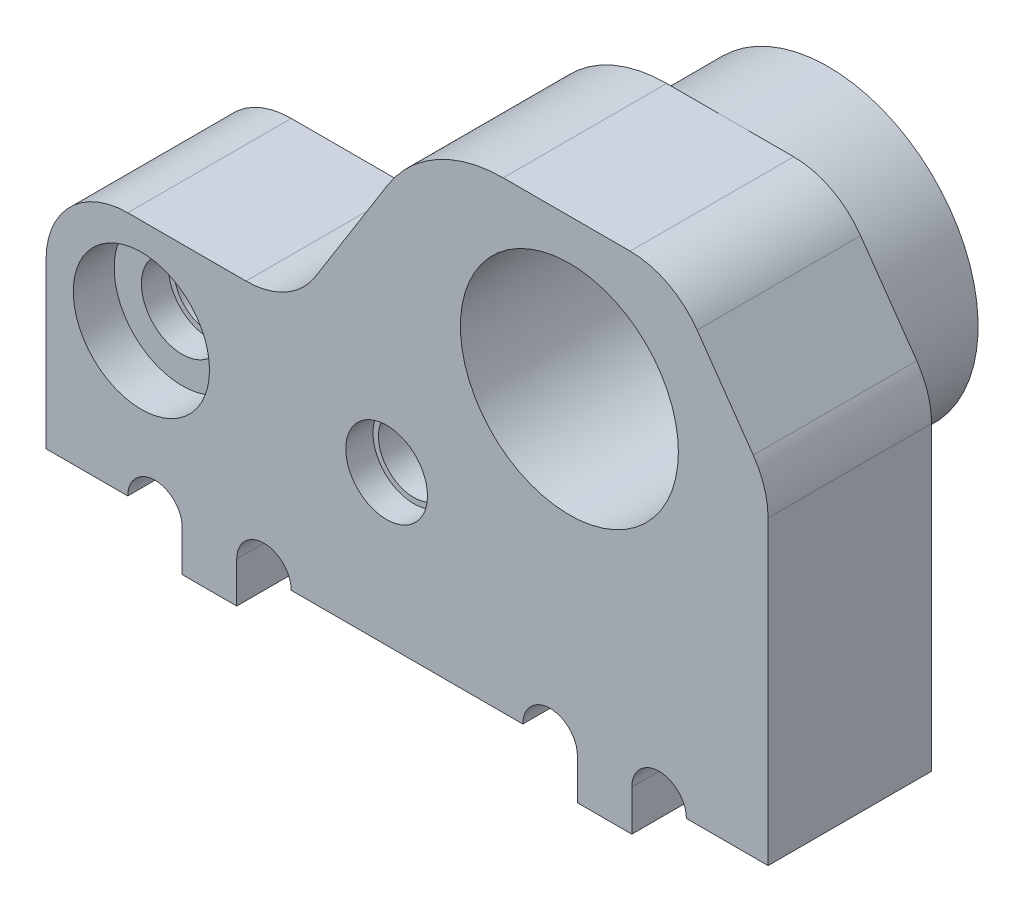
SolidWorks part; units mm, degrees
ref_plane "Front Plane" through (0, 0, 0) normal (0, 0, 1) x (1, 0, 0)
ref_plane "Top Plane" through (0, 0, 0) normal (0, 1, 0) x (1, 0, 0)
ref_plane "Right Plane" through (0, 0, 0) normal (1, 0, 0) x (0, 0, -1)
sketch "Sketch1" plane through (0, 0, 0) normal (0, 1, 0) x (1, 0, 0)
  line L1 (0, 0) -> (26.5, 0)
  line L2 (0, 0) -> (0, 6)
  line L3 (0, 6) -> (26.5, 6)
  line L4 (26.5, 0) -> (26.5, 6)
  dimension "D1" = 26.5
  dimension "D2" = 6
extrude "Boss-Extrude1" add sketch "Sketch1" along normal blind 17
ref_plane "Plane1" through (0, 5.5, 0) normal (0, 1, 0) x (1, 0, 0)
sketch "Sketch2" plane through (0, 0, 0) normal (0, 0, 1) x (1, 0, 0)
  line L0 (5.225, 5.5) -> (-5.225, 5.5) construction
  line L1 (26.5, 17) -> (26.5, 0) construction
  circle A0 centre (12.5, 5.5) radius 1.5
  circle A1 centre (12.5, 5.5) radius 9 construction
  dimension "D1" = 3
  dimension "D2" = 14
  dimension "D3" = 18
extrude "Cut-Extrude1" cut sketch "Sketch2" against normal blind 1
sketch "Sketch3" plane through (0, 0, -1) normal (0, 0, 1) x (1, 0, 0)
  circle A0 centre (12.5, 5.5) radius 1.3
  circle A1 centre (12.5, 5.5) radius 1.5 construction
  dimension "D1" = 0.2
extrude "Cut-Extrude2" cut sketch "Sketch3" against normal through all
sketch "Sketch4" plane through (0, 0, 0) normal (0, 0, 1) x (1, 0, 0)
  line L0 (5.225, 5.5) -> (-5.225, 5.5) construction
  circle A0 centre (19.2082, 11.5) radius 4
  circle A1 centre (12.5, 5.5) radius 1.5 construction
  point P2 (0, 0)
  point P3 (0, 0)
  dimension "D1" = 9
  dimension "D2" = 8
  dimension "D3" = 6
extrude "Cut-Extrude3" cut sketch "Sketch4" against normal through all
sketch "Sketch5" plane through (0, 0, 0) normal (0, 0, 1) x (1, 0, 0)
  line L0 (5.225, 5.5) -> (-5.225, 5.5) construction
  circle A0 centre (3.5, 5.5) radius 2.5
  circle A1 centre (12.5, 5.5) radius 1.5 construction
  point P2 (0, 0)
  dimension "D1" = 5
  dimension "D2" = 9
extrude "Cut-Extrude4" cut sketch "Sketch5" against normal blind 1.5
sketch "Sketch6" plane through (0, 0, -1.5) normal (0, 0, 1) x (1, 0, 0)
  circle A0 centre (3.5, 5.5) radius 1.5
  circle A1 centre (3.5, 5.5) radius 2.5 construction
  dimension "D1" = 3
extrude "Cut-Extrude8" cut sketch "Sketch6" against normal blind 1
sketch "Sketch7" plane through (0, 0, -2.5) normal (0, 0, 1) x (1, 0, 0)
  circle A0 centre (3.5, 5.5) radius 1.3
  circle A1 centre (3.5, 5.5) radius 1.5 construction
  dimension "D1" = 0.2
extrude "Cut-Extrude9" cut sketch "Sketch7" against normal through all
ref_plane "Plane2" through (0, 0, -9.3) normal (0, 0, -1) x (-1, 0, 0)
sketch "Sketch8" plane through (0, 0, -6) normal (0, 0, -1) x (-1, 0, 0)
  circle A0 centre (-3.5, 5.5) radius 2.5
  dimension "D1" = 5
extrude "Cut-Extrude10" cut sketch "Sketch8" against normal blind 1
sketch "Sketch9" plane through (0, 0, -5) normal (0, 0, -1) x (-1, 0, 0)
  circle A0 centre (-3.5, 5.5) radius 1.5
  dimension "D1" = 3
extrude "Cut-Extrude11" cut sketch "Sketch9" against normal blind 1
sketch "Sketch10" plane through (0, 0, -6) normal (0, 0, -1) x (-1, 0, 0)
  line L0 (-26.5, 17) -> (0, 17) construction
  circle A0 centre (-19.2082, 11.5) radius 5.5
  circle A1 centre (-19.2082, 11.5) radius 4 construction
  circle A2 centre (-19.2082, 11.5) radius 4
extrude "Boss-Extrude2" add sketch "Sketch10" along normal blind 3.5
sketch "Sketch11" plane through (0, 0, -6) normal (0, 0, -1) x (-1, 0, 0)
  circle A0 centre (-12.5, 5.5) radius 1.3 construction
  circle A1 centre (-12.5, 5.5) radius 1.3
  circle A2 centre (-12.5, 5.5) radius 3
  dimension "D1" = 6
extrude "Boss-Extrude4" add sketch "Sketch11" along normal blind 2
sketch "Sketch12" plane through (0, 0, -8) normal (0, 0, -1) x (-1, 0, 0)
  circle A0 centre (-12.5, 5.5) radius 1.5
  dimension "D1" = 3
extrude "Cut-Extrude12" cut sketch "Sketch12" against normal blind 1
sketch "Sketch17" plane through (0, 0, 0) normal (0, -1, 0) x (1, 0, 0)
  line L0 (10.175, 0) -> (-10.175, 0) construction
  line L1 (5, 0) -> (7, 0)
  line L2 (5, 0) -> (5, -6)
  line L3 (5, -6) -> (7, -6)
  line L4 (7, 0) -> (7, -6)
  line L5 (26.5, -6) -> (0, -6) construction
  line L6 (26.5, 0) -> (26.5, -6) construction
  line L7 (19.5, 0) -> (21.5, 0)
  line L8 (19.5, 0) -> (19.5, -6)
  line L9 (19.5, -6) -> (21.5, -6)
  line L10 (21.5, 0) -> (21.5, -6)
  line L11 (0, -5.236) -> (0, 5.236) construction
  dimension "D1" = 2
  dimension "D2" = 2
  dimension "D3" = 5
  dimension "D4" = 5
extrude "Boss-Extrude6" add sketch "Sketch17" along normal blind 1.5
sketch "Sketch18" plane through (0, 0, -6) normal (0, 0, -1) x (-1, 0, 0)
  line L0 (5.225, 0) -> (-5.225, 0) construction
  line L1 (-21.5, -1.5) -> (-21.5, 0) construction
  line L2 (-19.5, -1.5) -> (-19.5, 0) construction
  line L3 (-7, -1.5) -> (-7, 0) construction
  line L4 (-5, -1.5) -> (-5, 0) construction
  circle A0 centre (-22.5, 0) radius 1
  circle A1 centre (-18.5, 0) radius 1
  circle A2 centre (-8, 0) radius 1
  circle A3 centre (-4, 0) radius 1
  dimension "D1" = 2
extrude "Cut-Extrude17" cut sketch "Sketch18" against normal through all
chamfer "Chamfer2" distance 5 distance2 3.5 1 edges at (26.5, 17, -3)
fillet "Fillet11" radius 3 2 edges at (26.5, 12, -3) (23, 17, -3)
sketch "Sketch19" plane through (0, 0, -6) normal (0, 0, -1) x (-1, 0, 0)
  line L0 (-14.5471, 14.4196) -> (-9.9576, 7.0925)
  line L1 (-13.8002, 2.7964) -> (-21.5918, 6.5434)
  circle A0 centre (-12.5, 5.5) radius 3 construction
  circle A1 centre (-19.2082, 11.5) radius 5.5 construction
  arc A2 (-9.9576, 7.0925) -> (-13.8002, 2.7964) centre (-12.5, 5.5) ccw
  arc A3 (-21.5918, 6.5434) -> (-14.5471, 14.4196) centre (-19.2082, 11.5) ccw
extrude "Boss-Extrude7" add sketch "Sketch19" along normal up to surface (2 mm away) up to face at (11, 5.5, -8)
sketch "Sketch20" plane through (0, 0, -6) normal (0, 0, -1) x (-1, 0, 0)
  line L0 (5.225, 0) -> (-5.225, 0) construction
  line L1 (0, 17) -> (-14.011, 17)
  line L2 (0, 17) -> (0, 9)
  line L3 (0, 9) -> (-9, 9)
  line L5 (-9, 9) -> (-14.011, 17)
  line L6 (-19.2082, 17) -> (0, 17) construction
  line L7 (-9.9576, 7.0925) -> (-14.5471, 14.4196) construction
  point P12 (-14.2201, 17)
  dimension "D1" = 9
extrude "Cut-Extrude19" cut sketch "Sketch20" against normal through all
fillet "Fillet13" radius 5 1 edges at (14.011, 17, -3)
fillet "Fillet14" radius 3 1 edges at (9, 9, -3)
fillet "Fillet15" radius 3 1 edges at (0, 9, -3)
